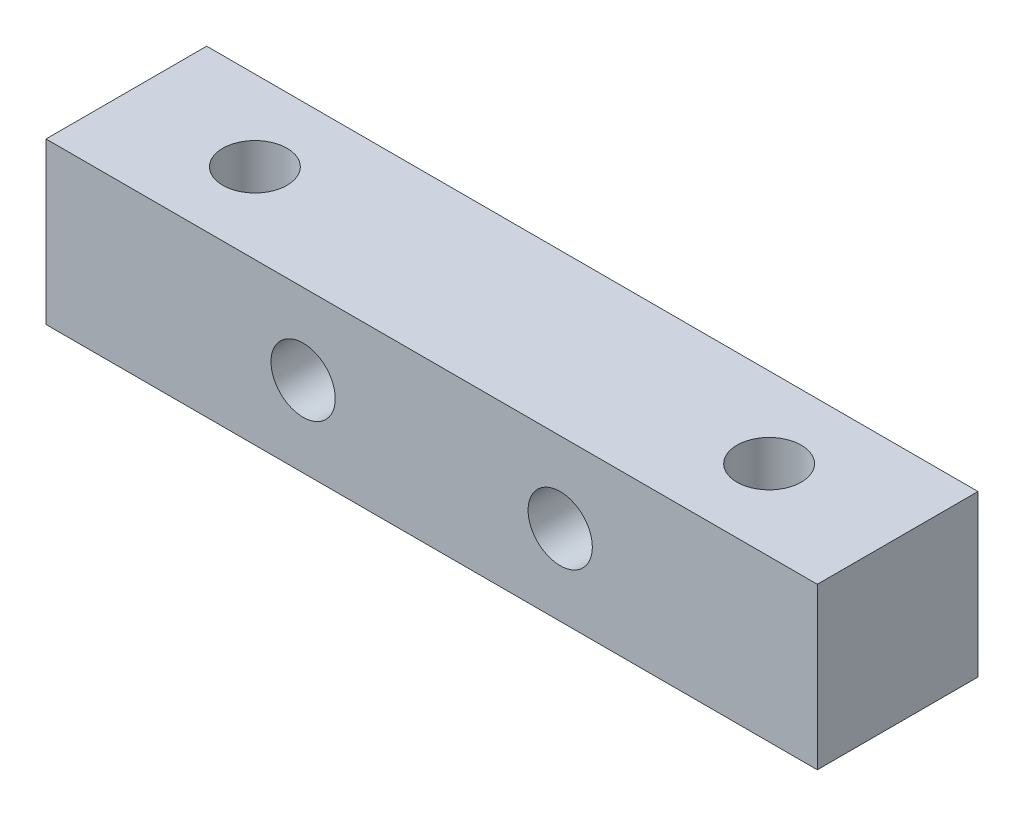
SolidWorks part; units mm, degrees
material "1060 合金"
ref_plane "前视基准面" through (0, 0, 0) normal (0, 0, 1) x (1, 0, 0)
ref_plane "上视基准面" through (0, 0, 0) normal (0, 1, 0) x (1, 0, 0)
ref_plane "右视基准面" through (0, 0, 0) normal (1, 0, 0) x (0, 0, -1)
other "Configuration Table"
sketch "草图1" plane through (0, 0, 0) normal (0, 1, 0) x (1, 0, 0)
  line L0 (-32.609, 0) -> (32.609, 0) construction
  line L1 (-24, -5) -> (24, -5)
  line L2 (-24, -5) -> (-24, 5)
  line L3 (-24, 5) -> (24, 5)
  line L4 (24, -5) -> (24, 5)
  line L5 (-24, -5) -> (24, 5) construction
  line L6 (-24, 5) -> (24, -5) construction
  circle A0 centre (16, 0) radius 2
  circle A1 centre (-16, 0) radius 2
  point P0 (0, 0)
  point P10 (0, 0)
  dimension "D3" = 4
  dimension "D4" = 4
  dimension "D5" = 32
  dimension "D1" = 48
  dimension "D2" = 10
  dimension "8" = 8
extrude "凸台-拉伸1" add sketch "草图1" along normal blind 10
sketch "草图2" plane through (0, 0, 5) normal (0, 0, 1) x (1, 0, 0)
  line L0 (0, 0) -> (0, 13.1149) construction
  line L2 (-24, 10) -> (-24, 0) construction
  line L3 (-24, 10) -> (24, 10) construction
  circle A0 centre (-8, 5) radius 2
  circle A1 centre (8, 5) radius 2
  dimension "D1" = 4
  dimension "D2" = 4
  dimension "D3" = 16
  dimension "D4" = 16
  dimension "D5" = 5
  dimension "D6" = 5
extrude "切除-拉伸1" cut sketch "草图2" against normal blind 10
